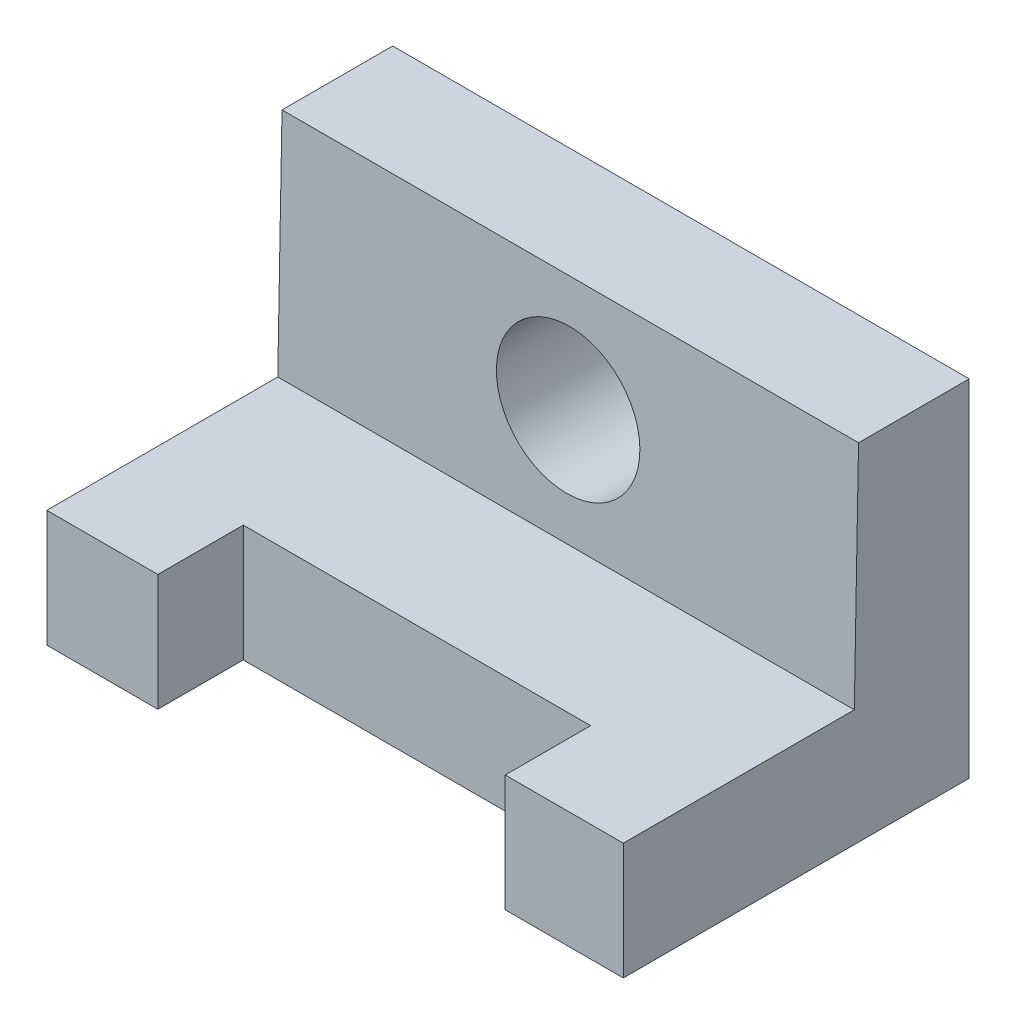
SolidWorks part; units mm, degrees
ref_plane "Front Plane" through (0, 0, 0) normal (0, 0, 1) x (1, 0, 0)
ref_plane "Top Plane" through (0, 0, 0) normal (0, 1, 0) x (1, 0, 0)
ref_plane "Right Plane" through (0, 0, 0) normal (1, 0, 0) x (0, 0, -1)
sketch "Sketch2" plane through (0, 0, 0) normal (1, 0, 0) x (0, 0, -1)
  line L0 (0, 0) -> (0, -60)
  line L1 (0, -60) -> (-60, -60)
  line L2 (-60, -60) -> (-60, -39.7469)
  line L3 (-60, -39.7469) -> (-19.9354, -39.7469)
  line L4 (-19.9354, -39.7469) -> (-19.1981, 0)
  line L5 (-19.1981, 0) -> (0, 0)
  dimension "D1" = 60
  dimension "D2" = 39.7537
  dimension "D3" = 40.0646
  dimension "D4" = 60
  dimension "D5" = 20.2531
extrude "Boss-Extrude1" add sketch "Sketch2" along normal blind 100 contours L5 L0 L1 L2 L3 L4
sketch "Sketch5" plane through (0, 0.356, 19.1915) normal (0, 0.0185, 0.9998) x (1, 0, 0)
  line L0 (0, -20.2329) -> (100, -20.2329) construction
  line L1 (0, -40.1098) -> (0, -0.3561) construction
  line L2 (100, -40.1098) -> (100, -0.3561) construction
  line L3 (100, -0.3561) -> (0, -0.3561) construction
  line L4 (100, -40.1098) -> (0, -40.1098) construction
  line L5 (50, -0.3561) -> (50, -40.1098) construction
  line L8 (-4.0619, -66.8464) -> (58.3658, -66.8464)
  line L9 (-4.0619, -66.8464) -> (-4.0619, -86.8951)
  line L10 (-4.0619, -86.8951) -> (58.3658, -86.8951)
  line L11 (58.3658, -66.8464) -> (58.3658, -86.8951)
  circle A0 centre (50, -20.2329) radius 12.443
extrude "Cut-Extrude1" cut sketch "Sketch5" against normal blind 100
sketch "Sketch6" plane through (0, -39.7469, 0) normal (0, 1, 0) x (1, 0, 0)
  line L5 (14.5479, -43.8052) -> (14.5479, -43.3821)
  line L6 (100, -60) -> (0, -60) construction
  line L7 (19.2658, -60) -> (79.5163, -60)
  line L8 (19.2658, -60) -> (19.2658, -45.184)
  line L9 (19.2658, -45.184) -> (79.5163, -45.184)
  line L10 (79.5163, -60) -> (79.5163, -45.184)
extrude "Cut-Extrude2" cut sketch "Sketch6" against normal blind 100 contours L7 L10 L9 L8
